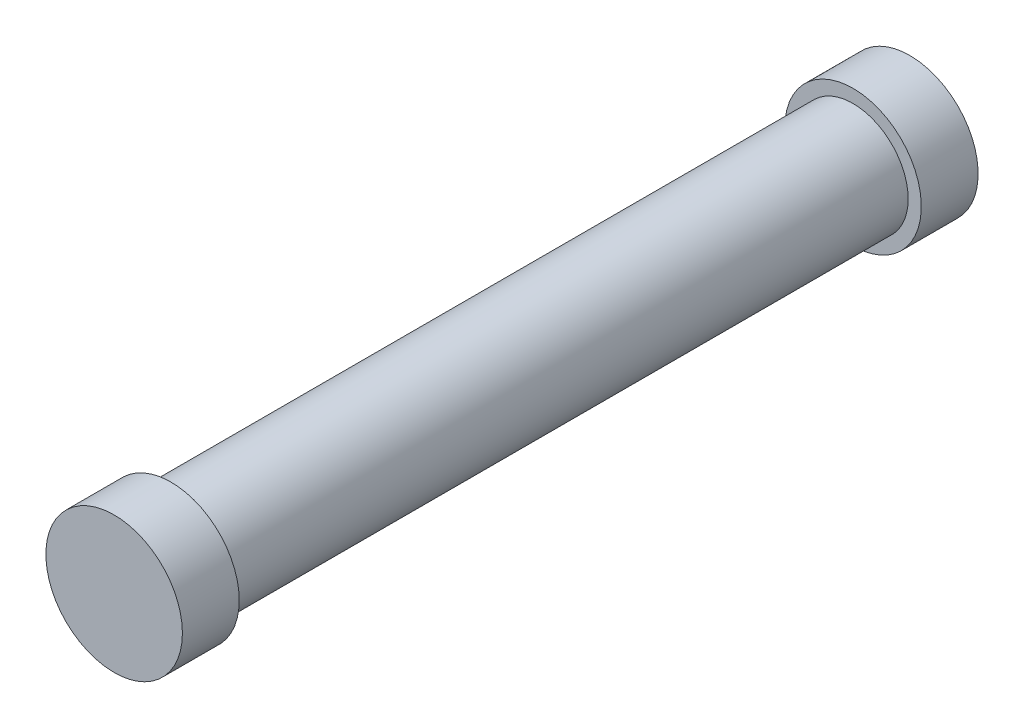
SolidWorks part; units mm, degrees
ref_plane "Front Plane" through (0, 0, 0) normal (0, 0, 1) x (1, 0, 0)
ref_plane "Top Plane" through (0, 0, 0) normal (0, 1, 0) x (1, 0, 0)
ref_plane "Right Plane" through (0, 0, 0) normal (1, 0, 0) x (0, 0, -1)
sketch "Sketch1" plane through (0, 0, 0) normal (0, 0, 1) x (1, 0, 0)
  circle A0 centre (0, 0) radius 2.91
extrude "Boss-Extrude1" add sketch "Sketch1" along normal blind 36
sketch "Sketch2" plane through (0, 0, 36) normal (0, 0, 1) x (1, 0, 0)
  circle A0 centre (0, 0) radius 3.6032
extrude "Boss-Extrude2" add sketch "Sketch2" along normal blind 3
sketch "Sketch3" plane through (0, 0, 0) normal (0, 0, -1) x (-1, 0, 0)
  circle A0 centre (0, 0) radius 3.6032
extrude "Boss-Extrude3" add sketch "Sketch3" along normal blind 3
